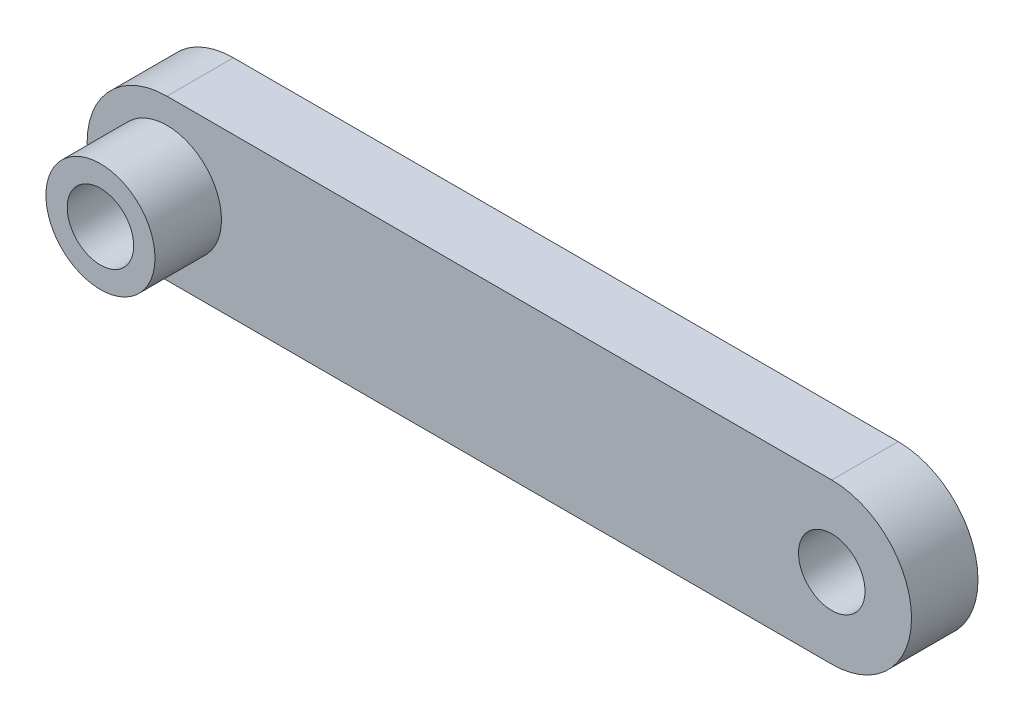
SolidWorks part; units mm, degrees
ref_plane "Front Plane" through (0, 0, 0) normal (0, 0, 1) x (1, 0, 0)
ref_plane "Top Plane" through (0, 0, 0) normal (0, 1, 0) x (1, 0, 0)
ref_plane "Right Plane" through (0, 0, 0) normal (1, 0, 0) x (0, 0, -1)
sketch "Sketch2" plane through (0, 0, 0) normal (0, 0, 1) x (1, 0, 0)
  line L0 (0, 0) -> (127, 0) construction
  line L1 (0, 15.24) -> (127, 15.24)
  line L2 (0, -15.24) -> (127, -15.24)
  arc A0 (0, 15.24) -> (0, -15.24) centre (0, 0) ccw
  arc A1 (127, -15.24) -> (127, 15.24) centre (127, 0) ccw
  point P3 (63.5, 0)
  dimension "D1" = 15.24
  dimension "D2" = 127
extrude "Boss-Extrude2" add sketch "Sketch2" along normal blind 12.7
sketch "Sketch4" plane through (0, 0, 12.7) normal (0, 0, 1) x (1, 0, 0)
  circle A0 centre (0, 0) radius 10.4194
extrude "Boss-Extrude3" add sketch "Sketch4" along normal blind 12.7
sketch "Sketch3" plane through (0, 0, 12.7) normal (0, 0, 1) x (1, 0, 0)
  circle A0 centre (0, 0) radius 6.35
  circle A1 centre (127, 0) radius 6.35
  dimension "D1" = 12.7
  dimension "D2" = 12.7
  dimension "D3" = 127
extrude "Cut-Extrude1" cut sketch "Sketch3" against normal through all and the other way through all
